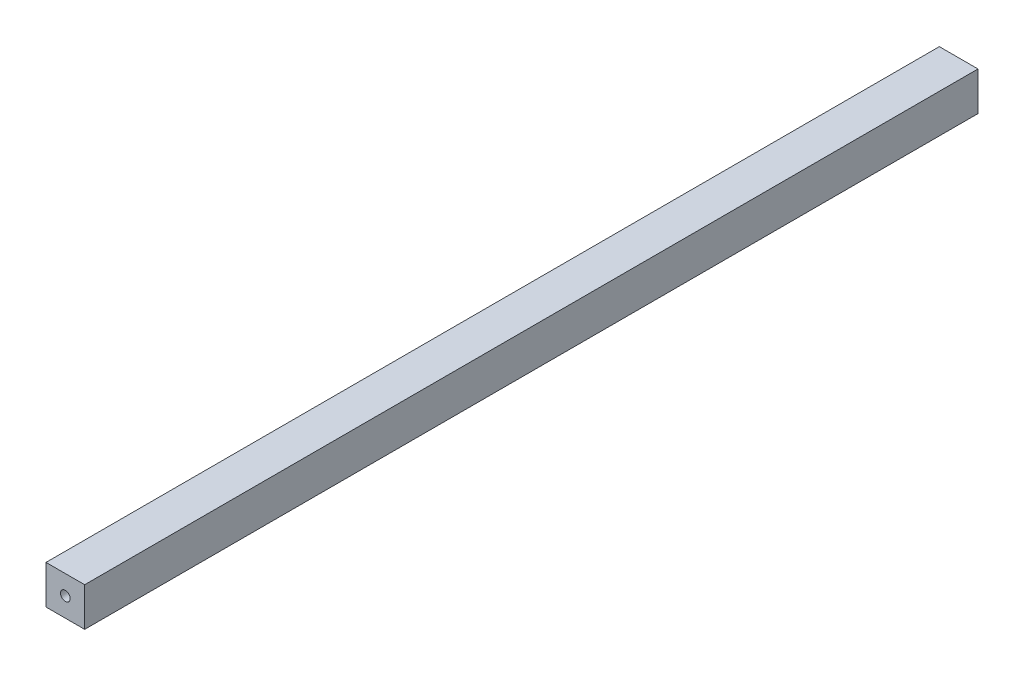
SolidWorks part; units mm, degrees
ref_plane "Plan de face" through (0, 0, 0) normal (0, 0, 1) x (1, 0, 0)
ref_plane "Plan de dessus" through (0, 0, 0) normal (0, 1, 0) x (1, 0, 0)
ref_plane "Plan de droite" through (0, 0, 0) normal (1, 0, 0) x (0, 0, -1)
sketch "Esquisse1" plane through (0, 0, 0) normal (0, 0, 1) x (1, 0, 0)
  line L0 (-5, 5) -> (5, -5) construction
  line L1 (-5, 5) -> (5, 5)
  line L2 (-5, 5) -> (-5, -5)
  line L3 (-5, -5) -> (5, -5)
  line L4 (5, 5) -> (5, -5)
  dimension "D1" = 10
extrude "Boss.-Extru.1" add sketch "Esquisse1" along normal offset from surface 2 and the other way offset from surface (115.5 mm away) 2
hole_wizard "Trou taraudé M3x0.51" positions "Esquisse2" profile "Esquisse3" tap size "M3x0.5" standard "Ansi Metric"
sketch "Esquisse2" plane through (0, 0, 115.5) normal (0, 0, 1) x (1, 0, 0)
  point P0 (0, 0)
sketch "Esquisse3" plane through (0, 0, 115.5) normal (1, 0, 0) x (0, -1, 0)
  line L0 (0, 0) -> (0, 8.5)
  line L1 (0, 8.5) -> (1.25, 8.5)
  line L2 (1.25, 8.5) -> (1.25, 0)
  line L5 (1.25, 0) -> (0, 0)
  line L10 (0, 8.5) -> (-1.25, 8.5) construction
  line L11 (0, -6.35) -> (0, 107.95) construction
  dimension "Diamètre du trou pour taraudage" = 2.5
  dimension "Profondeur du trou pour taraudage" = 8.5
  dimension "Angle de pointe" = 180
cosmetic thread "Filetage de perçage1" parameters "D1"=6, "D2"=3
hole_wizard "Trou taraudé M3x0.52" positions "Esquisse4" profile "Esquisse5" tap size "M3x0.5" standard "Ansi Metric"
sketch "Esquisse4" plane through (0, 0, -115.5) normal (0, 0, -1) x (-1, 0, 0)
  point P0 (0, 0)
sketch "Esquisse5" plane through (0, 0, -115.5) normal (1, 0, 0) x (0, 1, 0)
  line L0 (0, 0) -> (0, 8.5)
  line L1 (0, 8.5) -> (1.25, 8.5)
  line L2 (1.25, 8.5) -> (1.25, 0)
  line L5 (1.25, 0) -> (0, 0)
  line L10 (0, 8.5) -> (-1.25, 8.5) construction
  line L11 (0, -6.35) -> (0, 107.95) construction
  dimension "Diamètre du trou pour taraudage" = 2.5
  dimension "Profondeur du trou pour taraudage" = 8.5
  dimension "Angle de pointe" = 180
cosmetic thread "Filetage de perçage2" parameters "D1"=6, "D2"=3
